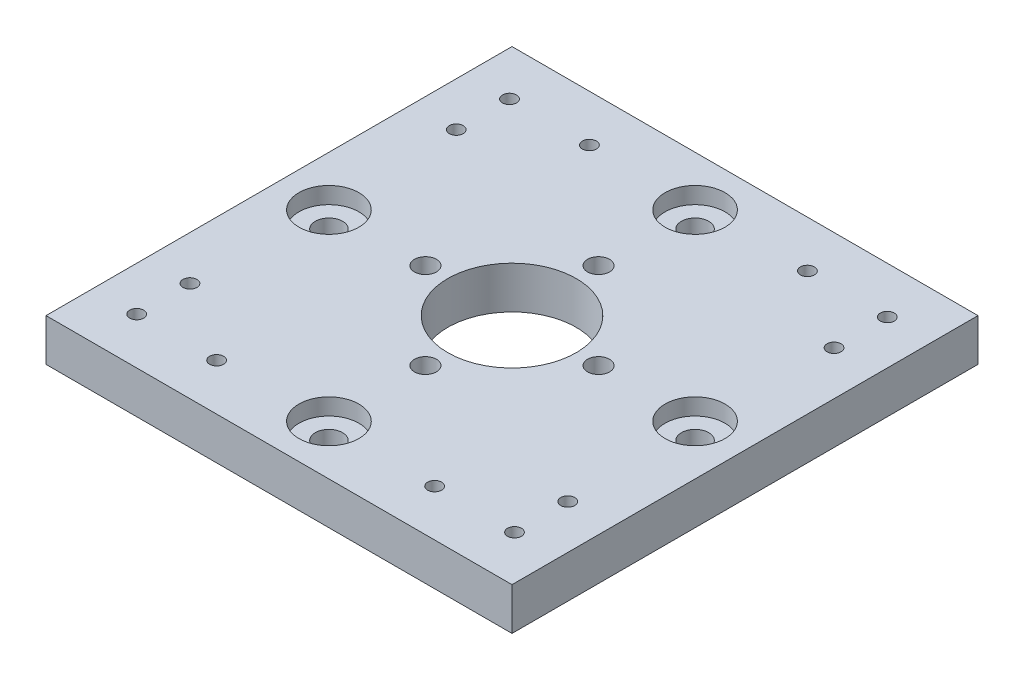
SolidWorks part; units mm, degrees
material "6061 Alloy"
ref_plane "Front Plane" through (0, 0, 0) normal (0, 0, 1) x (1, 0, 0)
ref_plane "Top Plane" through (0, 0, 0) normal (0, 1, 0) x (1, 0, 0)
ref_plane "Right Plane" through (0, 0, 0) normal (1, 0, 0) x (0, 0, -1)
sketch "Sketch1" plane through (0, 0, 0) normal (0, 1, 0) x (1, 0, 0)
  line L1 (-35, -35) -> (35, -35)
  line L2 (-35, -35) -> (-35, 35)
  line L3 (-35, 35) -> (35, 35)
  line L4 (35, -35) -> (35, 35)
  line L5 (-35, -35) -> (35, 35) construction
  line L6 (-35, 35) -> (35, -35) construction
  circle A1 centre (0, 0) radius 13
  circle A2 centre (0, 13) radius 1.65
  circle A3 centre (13, 0) radius 1.65
  circle A4 centre (0, -13) radius 1.65
  circle A5 centre (-13, 0) radius 1.65
  point P1 (0, 0)
  dimension "D1" = 26
  dimension "D2" = 3.3
  dimension "D3" = 70
  dimension "D4" = 70
extrude "Boss-Extrude1" add sketch "Sketch1" along normal blind 6.35
sketch "Sketch2" plane through (0, 6.35, 0) normal (0, 1, 0) x (1, 0, 0)
  line L0 (0, 0) -> (0, 50000) construction
  line L1 (0, 0) -> (-50000, 0) construction
  circle A0 centre (16.375, 28) radius 1.05
  circle A1 centre (28.375, 28) radius 1.05
  circle A2 centre (28.375, 20) radius 1.05
  circle A3 centre (-28.375, 20) radius 1.05
  circle A4 centre (-28.375, 28) radius 1.05
  circle A5 centre (-16.375, 28) radius 1.05
  circle A6 centre (28.375, -20) radius 1.05
  circle A7 centre (28.375, -28) radius 1.05
  circle A8 centre (16.375, -28) radius 1.05
  circle A9 centre (-16.375, -28) radius 1.05
  circle A10 centre (-28.375, -20) radius 1.05
  circle A11 centre (-28.375, -28) radius 1.05
  dimension "D1" = 2.1
  dimension "D2" = 8
  dimension "D3" = 12
  dimension "D5" = 16.375
  dimension "D4" = 20
extrude "Cut-Extrude1" cut sketch "Sketch2" against normal up to next
sketch "Sketch3" plane through (0, 6.35, 0) normal (0, 1, 0) x (1, 0, 0)
  circle A0 centre (0, 0) radius 9.65
  dimension "D1" = 19.3
extrude "Cut-Extrude2" cut sketch "Sketch3" against normal up to next
sketch "Sketch4" plane through (0, 6.35, 0) normal (0, 1, 0) x (1, 0, 0)
  circle A0 centre (0, 0) radius 27.5
  circle A1 centre (0, 27.5) radius 2.05
  circle A2 centre (27.5, 0) radius 2.05
  circle A3 centre (0, -27.5) radius 2.05
  circle A4 centre (-27.5, 0) radius 2.05
  point P13 (0, 0)
  dimension "D1" = 55
  dimension "D2" = 4.1
  dimension "D3" = 4
extrude "Cut-Extrude3" cut sketch "Sketch4" against normal up to next contours A0 A4 | A0 A4 | A0 A1 | A0 A1 | A0 A2 | A0 A2 | A0 A3 | A0 A3
sketch "Sketch5" plane through (0, 6.35, 0) normal (0, 1, 0) x (1, 0, 0)
  circle A0 centre (0, 27.5) radius 4.5
  circle A1 centre (27.5, 0) radius 4.5
  circle A2 centre (0, -27.5) radius 4.5
  circle A3 centre (-27.5, 0) radius 4.5
  dimension "D1" = 9
extrude "Cut-Extrude4" cut sketch "Sketch5" against normal blind 2.5
